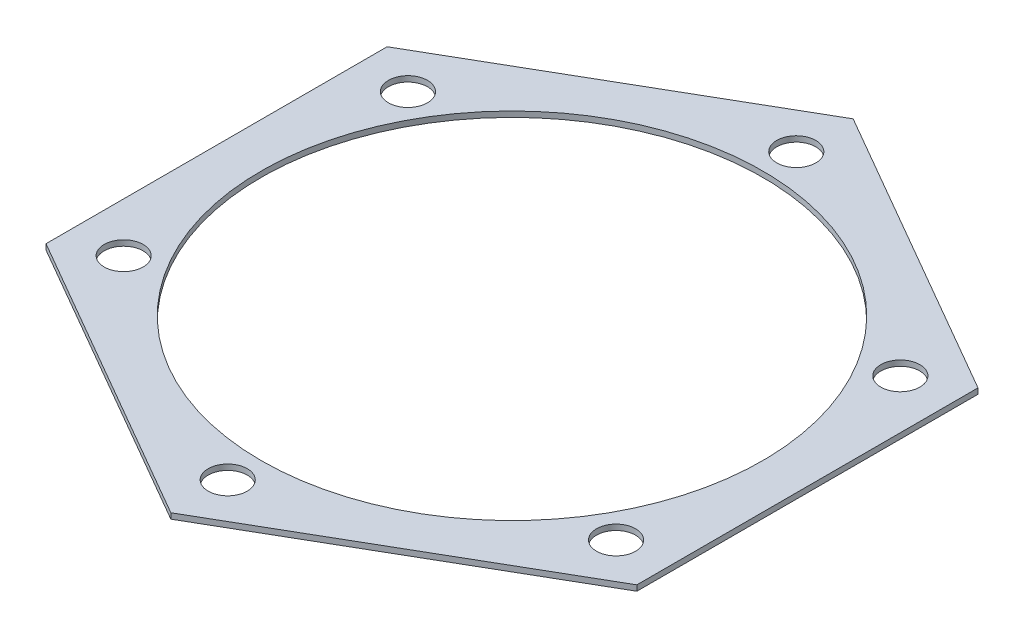
SolidWorks part; units mm, degrees
ref_plane "Front Plane" through (0, 0, 0) normal (0, 0, 1) x (1, 0, 0)
ref_plane "Top Plane" through (0, 0, 0) normal (0, 1, 0) x (1, 0, 0)
ref_plane "Right Plane" through (0, 0, 0) normal (1, 0, 0) x (0, 0, -1)
sketch "Sketch1" plane through (0, 0, 0) normal (0, 1, 0) x (1, 0, 0)
  line L1 (0, 61.1991) -> (-53, 30.5996)
  line L2 (-53, 30.5996) -> (-53, -30.5996)
  line L3 (-53, -30.5996) -> (0, -61.1991)
  line L4 (0, -61.1991) -> (53, -30.5996)
  line L5 (53, -30.5996) -> (53, 30.5996)
  line L6 (53, 30.5996) -> (0, 61.1991)
  circle A0 centre (0, 0) radius 53 construction
  dimension "D1" = 106
extrude "Boss-Extrude1" add sketch "Sketch1" along normal blind 1
sketch "Sketch2" plane through (0, 1, 0) normal (0, 1, 0) x (1, 0, 0)
  circle A0 centre (0, 0) radius 51 construction
  circle A1 centre (0, 0) radius 45
  circle A2 centre (0, 51) radius 3.5
  circle A3 centre (44.1673, 25.5) radius 3.5
  circle A4 centre (44.1673, -25.5) radius 3.5
  circle A5 centre (0, -51) radius 3.5
  circle A6 centre (-44.1673, -25.5) radius 3.5
  circle A7 centre (-44.1673, 25.5) radius 3.5
  point P18 (0, 0)
  dimension "D1" = 102
  dimension "D2" = 90
  dimension "D3" = 7
  dimension "D4" = 6
extrude "Cut-Extrude1" cut sketch "Sketch2" against normal through all
